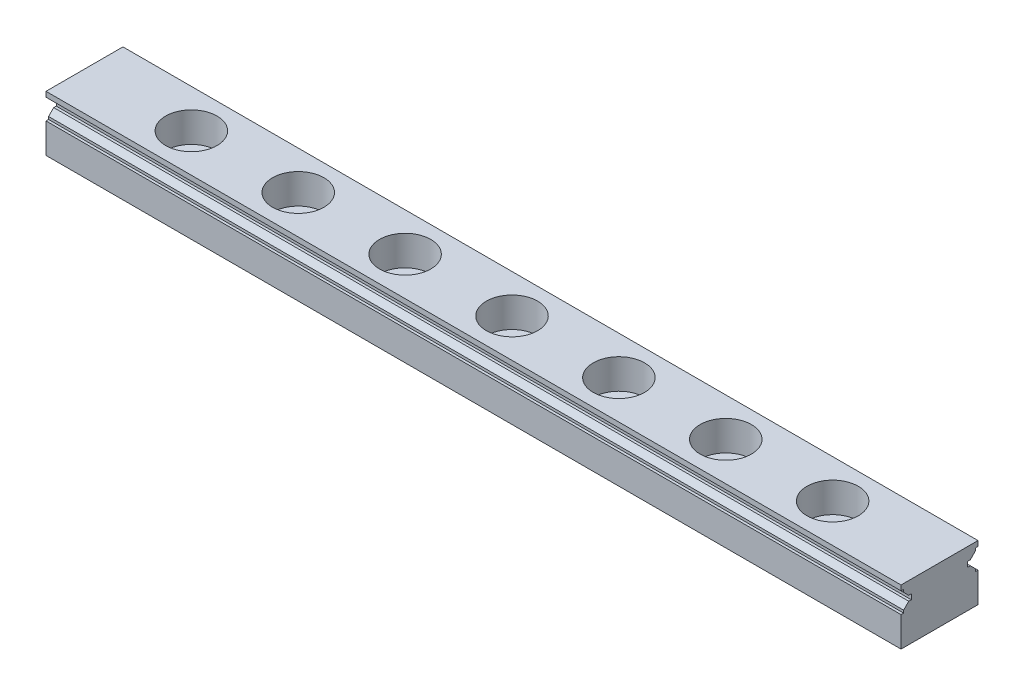
SolidWorks part; units mm, degrees
ref_plane "Plan de face" through (0, 0, 0) normal (0, 0, 1) x (1, 0, 0)
ref_plane "Plan de dessus" through (0, 0, 0) normal (0, 1, 0) x (1, 0, 0)
ref_plane "Plan de droite" through (0, 0, 0) normal (1, 0, 0) x (0, 0, -1)
other "L"
other "e"
other "Nombre"
sketch "Esquisse1" plane through (0, 0, 0) normal (1, 0, 0) x (0, 0, -1)
  line L0 (0, 0) -> (0, 10.8057) construction
  line L1 (-4.5, 0) -> (4.5, 0)
  line L2 (4.5, 0) -> (4.5, 3.5)
  line L3 (4.5, 3.5) -> (3.6, 4.4)
  line L4 (3.6, 4.4) -> (3.3, 4.4)
  line L5 (3.3, 4.4) -> (3.3, 5)
  line L6 (4.5, 5.9) -> (3.6, 5)
  line L7 (3.6, 5) -> (3.3, 5)
  line L8 (4.5, 5.9) -> (4.5, 6.5)
  line L9 (4.5, 6.5) -> (-4.5, 6.5)
  line L10 (3.3, 4.7) -> (8.4079, 4.7) construction
  line L11 (-4.5, 5.9) -> (-4.5, 6.5)
  line L12 (-4.5, 5.9) -> (-3.6, 5)
  line L13 (-3.6, 5) -> (-3.3, 5)
  line L14 (-3.3, 4.4) -> (-3.3, 5)
  line L15 (-3.6, 4.4) -> (-3.3, 4.4)
  line L16 (-4.5, 3.5) -> (-3.6, 4.4)
  line L17 (-4.5, 0) -> (-4.5, 3.5)
  point P18 (0, 6.5)
  dimension "D1" = 6.5
  dimension "D2" = 9
  dimension "D3" = 0.6
  dimension "D4" = 1.2
  dimension "D5" = 2.4
  dimension "D6" = 4.7
extrude "Boss.-Extru.1" add sketch "Esquisse1" along normal blind 100
sketch "Esquisse2" plane through (0, 0, 0) normal (1, 0, 0) x (0, 0, -1)
  line L0 (3.3, 5) -> (3.6, 5) construction
  line L1 (4.5, 5.9) -> (4.2, 5.9)
  line L2 (4.5, 5.9) -> (4.5, 3.5)
  line L3 (4.5, 3.5) -> (4.2, 3.5)
  line L4 (4.2, 5.9) -> (4.2, 3.5)
  line L5 (0, 0) -> (0, 7.1139) construction
  line L6 (-4.5, 5.9) -> (-4.2, 5.9)
  line L7 (-4.5, 5.9) -> (-4.5, 3.5)
  line L8 (-4.5, 3.5) -> (-4.2, 3.5)
  line L9 (-4.2, 5.9) -> (-4.2, 3.5)
extrude "Enlèv. mat.-Extru.1" cut sketch "Esquisse2" along normal through all
hole_wizard "Chambrage pour vis à tête hexagonale M31" positions "Esquisse3" profile "Esquisse4" counterbore size "M3" standard "ISO" end condition through all
sketch "Esquisse3" plane through (0, 6.5, 0) normal (0, 1, 0) x (1, 0, 0)
  line L0 (0, 4.5) -> (0, -4.5) construction
  point P0 (12.5, 0)
  point P6 (0, 0)
  dimension "D1" = 12.5
sketch "Esquisse4" plane through (12.5, 6.5, 0) normal (1, 0, 0) x (0, 0, 1)
  line L0 (0, 0) -> (0, 6.5)
  line L1 (0, 6.5) -> (1.75, 6.5)
  line L3 (1.75, 6.5) -> (1.75, 3.5)
  line L4 (1.75, 3.5) -> (3, 3.5)
  line L5 (3, 3.5) -> (3, 0)
  line L7 (3, 0) -> (0, 0)
  line L11 (0, -6.35) -> (0, 107.95) construction
  dimension "Diamètre du perçage jusqu'au prochain" = 3.5
  dimension "Profondeur du perçage jusqu'au prochain" = 6.5
  dimension "Diamètre du chambrage" = 6
  dimension "Profondeur du chambrage" = 3.5
pattern_linear "Répétition linéaire1" count 7 spacing 12.5 along (1, 0, 0) of "Chambrage pour vis à tête hexagonale M31"
ref_plane "SYM" through (50, 0, 0) normal (-1, 0, 0) x (0, 0, 1)
move or copy body "Corps-Déplacer/Copier1" [suppressed] bodies to move or copy 104
equation "\"D1@SYM\"=\"D1@Boss.-Extru.1\"/2"
